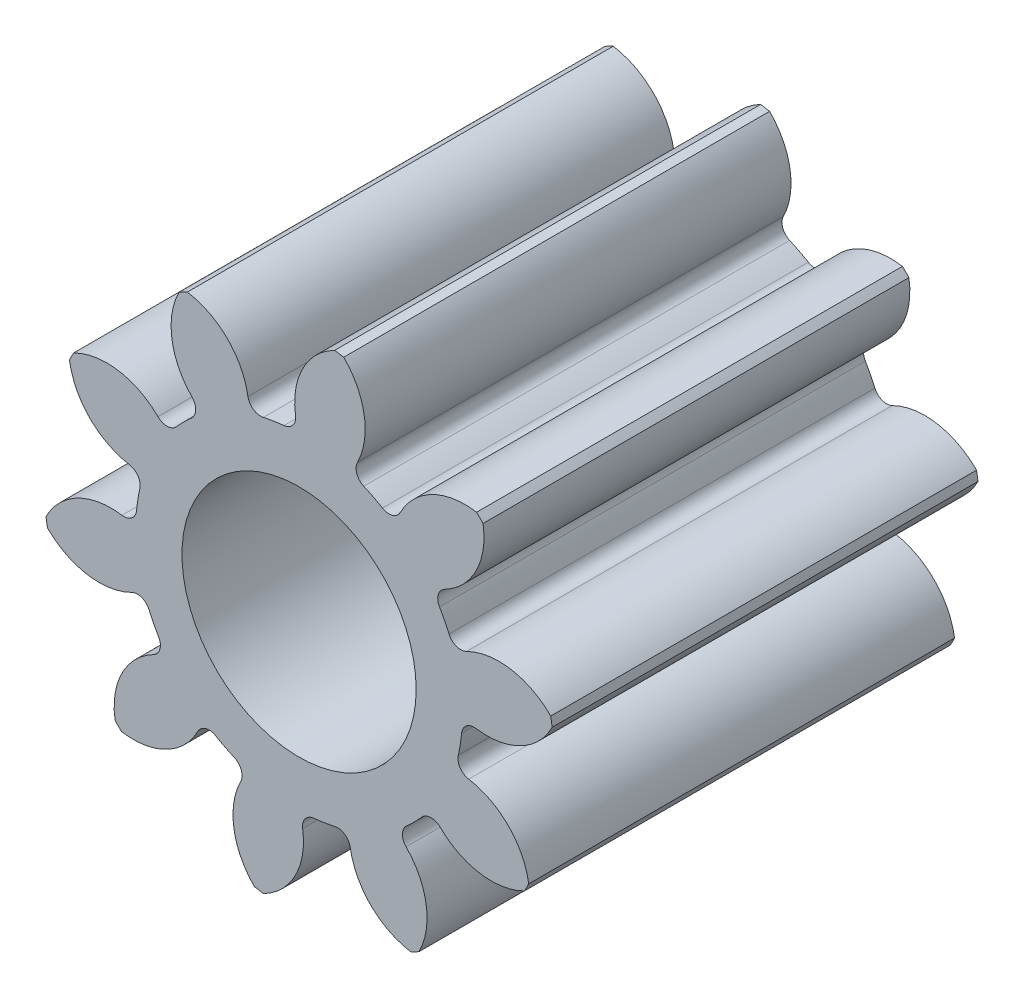
SolidWorks part; units mm, degrees
ref_plane "Alzado" through (0, 0, 0) normal (0, 0, 1) x (1, 0, 0)
ref_plane "Planta" through (0, 0, 0) normal (0, 1, 0) x (1, 0, 0)
ref_plane "Vista lateral" through (0, 0, 0) normal (1, 0, 0) x (0, 0, -1)
sketch "Croquis1" plane through (0, 0, 0) normal (0, 0, 1) x (1, 0, 0)
  line L0 (0, 31.7905) -> (0, 0) construction
  line L1 (0, 0) -> (4.9696, 31.2448) construction
  line L2 (0, 5) -> (1.607, 4.4151) construction
  line L3 (1.5513, 4.7533) -> (-0.1579, 4.6958) construction
  circle A0 centre (0, 0) radius 4.6985 construction
  circle A1 centre (0, 0) radius 5 construction
  circle A2 centre (0, 0) radius 6 construction
  circle A3 centre (0, 0) radius 3.833 construction
  arc A4 (0.8359, 5.9415) -> (-0.001, 3.833) centre (1.607, 4.4151) ccw
  arc A5 (1.0488, 5.9076) -> (1.1902, 3.6435) centre (-0.1579, 4.6958) cw
  arc A6 (1.0488, 5.9076) -> (0.8359, 5.9415) centre (0, 0) ccw
  arc A7 (1.1902, 3.6435) -> (0, 3.833) centre (0, 0) cw
  circle A8 centre (0, 0) radius 2.75
  dimension "D1" = 12
  dimension "D2" = 10
  dimension "D3" = 9.3969
  dimension "D4" = 7.666
  dimension "D6" = 5.5
  dimension "D5" = 1.5708
extrude "Saliente-Extruir1" add sketch "Croquis1" along normal blind 10
fillet "Redondeo1" radius 0.3 2 edges at (-0.001, 3.833, 5) (1.1902, 3.6435, 5)
pattern_circular "MatrizC1" count 10 over 360 about axis through (0, 0, 0) along (0, 0, 1) of "Saliente-Extruir1", "Redondeo1"
